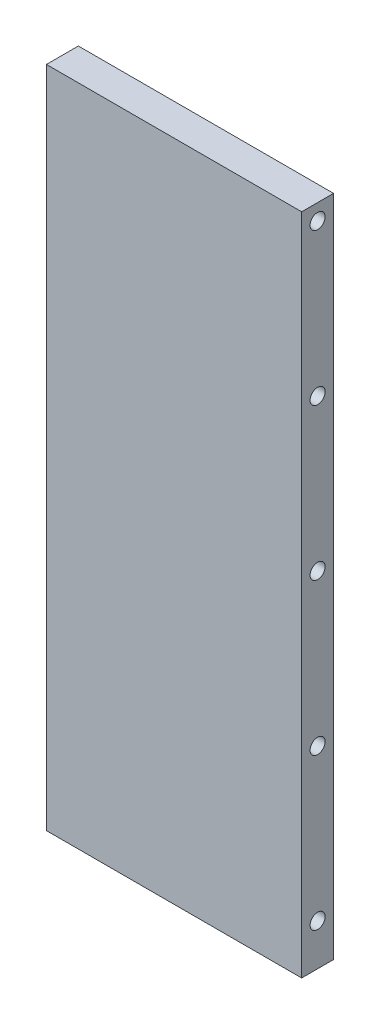
SolidWorks part; units mm, degrees
material "PLA"
ref_plane "Alzado" through (0, 0, 0) normal (0, 0, 1) x (1, 0, 0)
ref_plane "Planta" through (0, 0, 0) normal (0, 1, 0) x (1, 0, 0)
ref_plane "Vista lateral" through (0, 0, 0) normal (1, 0, 0) x (0, 0, -1)
sketch "Croquis1" plane through (0, 0, 0) normal (0, 0, 1) x (1, 0, 0)
  line L1 (0, 0) -> (80, 0)
  line L2 (0, 0) -> (0, 200)
  line L3 (0, 200) -> (80, 200)
  line L4 (80, 0) -> (80, 200)
  dimension "D1" = 200
  dimension "D2" = 80
extrude "Saliente-Extruir1" add sketch "Croquis1" along normal blind 10
sketch "Croquis3" plane through (0, 0, 0) normal (-1, 0, 0) x (0, 0, 1)
  line L1 (10, 200) -> (0, 200) construction
  line L3 (10, 200) -> (10, 0) construction
  line L4 (10, 0) -> (0, 0) construction
  circle A0 centre (5, 195) radius 2.35
  circle A1 centre (5, 147.5) radius 2.35
  circle A2 centre (5, 100) radius 2.35
  circle A3 centre (5, 52.5) radius 2.35
  circle A4 centre (5, 5) radius 2.35
  dimension "D1" = 4.7
  dimension "D2" = 5
  dimension "D3" = 5
  dimension "D5" = 5
  dimension "D4" = 5
extrude "Cortar-Extruir2" cut sketch "Croquis3" against normal blind 5
sketch "Croquis4" plane through (80, 0, 0) normal (1, 0, 0) x (0, 0, -1)
  circle A0 centre (-5, 195) radius 2.35
  circle A1 centre (-5, 147.5) radius 2.35
  circle A2 centre (-5, 100) radius 2.35
  circle A3 centre (-5, 52.5) radius 2.35
  circle A4 centre (-5, 5) radius 2.35
  dimension "D1" = 4.7
  dimension "D2" = 4.7
  dimension "D3" = 4.7
  dimension "D4" = 4.7
  dimension "D5" = 4.7
extrude "Cortar-Extruir3" cut sketch "Croquis4" against normal blind 5
sketch "Croquis5" plane through (0, 0, 0) normal (0, 0, -1) x (-1, 0, 0)
  line L0 (-80, 0) -> (0, 0)
  line L1 (0, 0) -> (0, -8)
  line L2 (0, -8) -> (-80, -8)
  line L3 (-80, -8) -> (-80, 0)
  dimension "D1" = 8
extrude "Saliente-Extruir2" add sketch "Croquis5" against normal blind 10
